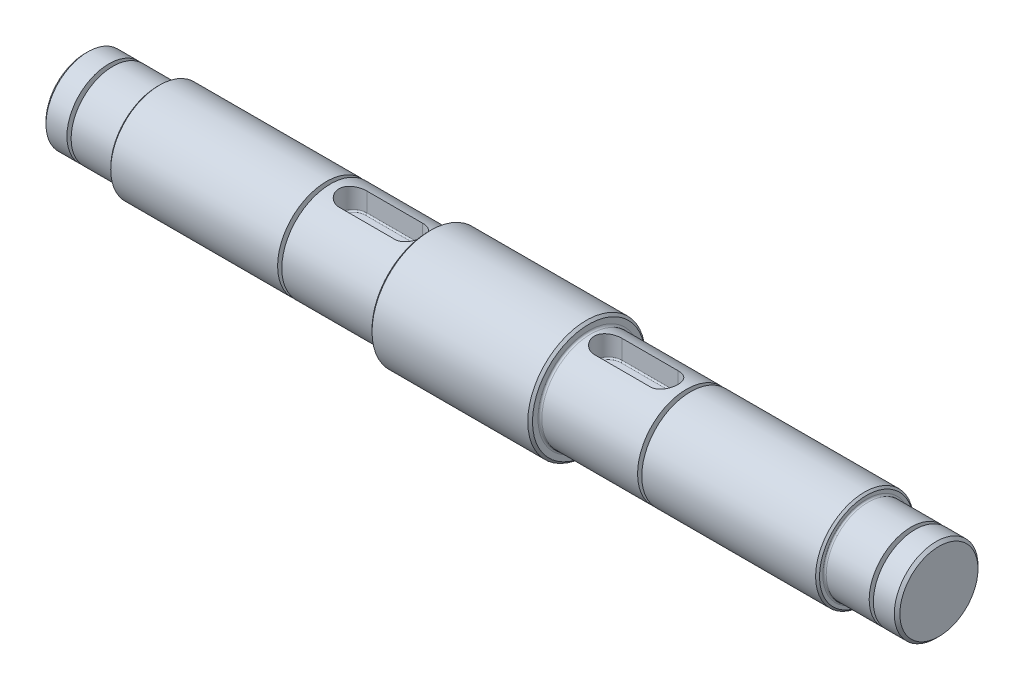
SolidWorks part; units mm, degrees
ref_plane "Front Plane" through (0, 0, 0) normal (0, 0, 1) x (1, 0, 0)
ref_plane "Top Plane" through (0, 0, 0) normal (0, 1, 0) x (1, 0, 0)
ref_plane "Right Plane" through (0, 0, 0) normal (1, 0, 0) x (0, 0, -1)
sketch "Sketch1" plane through (0, 0, 0) normal (0, 0, 1) x (1, 0, 0)
  line L0 (-143, 0) -> (143, 0) construction
  line L1 (-143, 0) -> (-143, 15)
  line L2 (-143, 15) -> (-127, 15)
  line L3 (-127, 15) -> (-127, 17.5)
  line L4 (-127, 17.5) -> (-66.5, 17.5)
  line L5 (-30, 17.5) -> (-30, 21)
  line L6 (-30, 21) -> (27.5, 21)
  line L7 (27.5, 21) -> (27.5, 17.5)
  line L8 (27.5, 17.5) -> (62.5, 17.5)
  line L9 (127, 17.5) -> (127, 15)
  line L10 (127, 15) -> (143, 15)
  line L11 (143, 15) -> (143, 0)
  line L12 (143, 0) -> (-143, 0)
  line L13 (-65, 17.5) -> (-65, 0) construction
  line L14 (-65, 17.5) -> (-30, 17.5)
  line L15 (62.5, 17.5) -> (62.5, 0) construction
  line L16 (64, 17.5) -> (127, 17.5)
  line L17 (-65, 17.5) -> (-65, 13.6)
  line L18 (-65, 13.6) -> (-66.5, 13.6)
  line L19 (-66.5, 13.6) -> (-66.5, 17.5)
  line L20 (62.5, 17.5) -> (62.5, 13.6)
  line L21 (62.5, 13.6) -> (64, 13.6)
  line L22 (64, 13.6) -> (64, 17.5)
  point P4 (0, 0)
  dimension "D13" = 3.9
  dimension "D15" = 3.9
  dimension "D1" = 286
  dimension "D2" = 16
  dimension "D3" = 99.5
  dimension "D4" = 15
  dimension "D5" = 17.5
  dimension "D6" = 21
  dimension "D7" = 57.5
  dimension "D8" = 17.5
  dimension "D9" = 97
  dimension "D10" = 16
  dimension "D11" = 15
  dimension "D12" = 35
  dimension "D14" = 35
  dimension "D16" = 1.5
  dimension "D17" = 1.5
revolve "Revolve1" add sketch "Sketch1" angle 360 about L0
fillet "Fillet1" [suppressed] radius 3
fillet "Fillet2" [suppressed] radius 3
fillet "Fillet3" [suppressed] radius 2.3
fillet "Fillet4" [suppressed] radius 2.3
sketch "Sketch2" plane through (-143, 0, 0) normal (-1, 0, 0) x (0, 0, 1)
  circle A1 centre (0, 0) radius 15
  circle A2 centre (0, 0) radius 15
  dimension "D1" = 0
extrude "Boss-Extrude1" add sketch "Sketch2" along normal blind 10 separate body
sketch "Sketch4" plane through (0, 0, 0) normal (0, 0, 1) x (1, 0, 0)
  line L0 (-143, 15) -> (-143, 11.5)
  line L1 (-143, 15) -> (-143, -15) construction
  line L2 (-143, 11.5) -> (-144.5, 11.5)
  line L3 (-144.5, 11.5) -> (-144.5, 15)
  line L4 (-143, 15) -> (-153, 15) construction
  line L5 (-144.5, 15) -> (-143, 15)
  line L6 (-153, 0) -> (0, 0) construction
  line L7 (-153, 15) -> (-153, -15) construction
  dimension "D1" = 1.5
  dimension "D2" = 3.5
revolve "Cut-Revolve1" cut sketch "Sketch4" angle 360 about L6
sketch "Sketch5" plane through (143, 0, 0) normal (1, 0, 0) x (0, 0, -1)
  circle A1 centre (0, 0) radius 15
  circle A2 centre (0, 0) radius 15
  dimension "D1" = 0
extrude "Boss-Extrude2" add sketch "Sketch5" along normal blind 10 separate body
sketch "Sketch6" plane through (0, 0, 0) normal (0, 0, 1) x (1, 0, 0)
  line L0 (143, 15) -> (143, 11.5)
  line L1 (143, 15) -> (143, -15) construction
  line L2 (143, 11.5) -> (144.5, 11.5)
  line L3 (144.5, 11.5) -> (144.5, 15)
  line L4 (153, 15) -> (143, 15) construction
  line L5 (144.5, 15) -> (143, 15)
  line L6 (-153, 0) -> (153, 0) construction
  line L7 (-153, 15) -> (-153, -15) construction
  line L8 (153, -15) -> (153, 15) construction
  dimension "D1" = 3.5
  dimension "D2" = 1.5
revolve "Cut-Revolve2" cut sketch "Sketch6" angle 360 about L6
ref_plane "Plane1" through (-37, 0, 0) normal (-1, 0, 0) x (0, 0, 1)
sketch "Sketch7" plane through (-37, 0, 0) normal (-1, 0, 0) x (0, 0, 1)
  line L0 (0, 17.5) -> (0, 0) construction
  line L1 (0, 17.5) -> (0, 9.5) construction
  line L2 (-5, 9.5) -> (5, 9.5)
  line L3 (5, 9.5) -> (5, 16.7705)
  line L4 (-5, 9.5) -> (-5, 16.7705)
  circle A0 centre (0, 0) radius 17.5 construction
  arc A1 (5, 16.7705) -> (-5, 16.7705) centre (0, 0) ccw
  point P8 (0, 9.5)
  dimension "D1" = 8
  dimension "D2" = 10
extrude "Cut-Extrude1" cut sketch "Sketch7" along normal blind 20
ref_plane "Plane2" through (34.5, 0, 0) normal (1, 0, 0) x (0, 0, -1)
sketch "Sketch8" plane through (34.5, 0, 0) normal (1, 0, 0) x (0, 0, -1)
  line L0 (0, 0) -> (0, 17.5) construction
  line L1 (0, 17.5) -> (0, 9.5) construction
  line L2 (-5, 9.5) -> (5, 9.5)
  line L3 (5, 9.5) -> (5, 16.7705)
  line L4 (-5, 9.5) -> (-5, 16.7705)
  circle A0 centre (0, 0) radius 17.5 construction
  arc A1 (5, 16.7705) -> (-5, 16.7705) centre (0, 0) ccw
  point P8 (0, 9.5)
  dimension "D1" = 10
  dimension "D2" = 8
extrude "Cut-Extrude2" cut sketch "Sketch8" along normal blind 20
fillet "Fillet5" radius 0.6 1 edges at (-127, 0, 15)
chamfer "Chamfer1" distance 0.7 angle 45 1 edges at (-127, 0, 17.5)
fillet "Fillet6" radius 0.7 1 edges at (-30, 0, 17.5)
chamfer "Chamfer2" distance 0.84 angle 45 1 edges at (-30, 0, 21)
fillet "Fillet7" radius 0.7 1 edges at (27.5, 0, 17.5)
chamfer "Chamfer3" distance 0.84 angle 45 1 edges at (27.5, 0, 21)
chamfer "Chamfer4" distance 0.7 angle 45 1 edges at (127, 0, 17.5)
fillet "Fillet8" radius 0.6 1 edges at (127, 0, 15)
ref_plane "Plane3" through (0, 17.5, 0) normal (0, 1, 0) x (1, 0, 0)
sketch "Sketch10" plane through (0, 17.5, 0) normal (0, 1, 0) x (1, 0, 0)
  line L0 (-57, 5) -> (-57, -5) construction
  line L1 (-37, 5) -> (-37, -5) construction
  line L2 (-57, 5) -> (-57, -5)
  line L3 (-37, 5) -> (-37, -5)
  arc A0 (-57, 5) -> (-57, -5) centre (-57, 0) ccw
  arc A1 (-37, -5) -> (-37, 5) centre (-37, 0) ccw
  dimension "D1" = 10
extrude "Cut-Extrude3" cut sketch "Sketch10" against normal up to surface (8 mm away) up to face at (-47, 9.5, 0)
ref_plane "Plane4" through (0, 17.5, 0) normal (0, 1, 0) x (1, 0, 0)
sketch "Sketch11" plane through (0, 17.5, 0) normal (0, 1, 0) x (1, 0, 0)
  line L0 (34.5, -5) -> (34.5, 5) construction
  line L1 (54.5, -5) -> (54.5, 5) construction
  line L2 (34.5, 5) -> (34.5, -5)
  line L3 (54.5, 5) -> (54.5, -5)
  arc A0 (34.5, 5) -> (34.5, -5) centre (34.5, 0) ccw
  arc A1 (54.5, -5) -> (54.5, 5) centre (54.5, 0) ccw
extrude "Cut-Extrude4" cut sketch "Sketch11" against normal up to surface (8 mm away) up to face at (44.5, 9.5, 0)
fillet "Fillet9" radius 0.4 1 edges at (144.5, 0, 11.5)
sketch "Sketch12" plane through (0, 0, 0) normal (0, 0, 1) x (1, 0, 0)
  line L0 (153, 0) -> (64, 0) construction
  line L1 (153, -15) -> (153, 15) construction
  line L2 (64, 13.6) -> (64, -13.6) construction
  line L6 (143, 11.9) -> (143, 11.5)
  line L7 (143.4, 11.5) -> (143, 11.5)
  arc A0 (143.4, 11.5) -> (143, 11.9) centre (143.4, 11.9) cw
  dimension "D1" = 0.4
revolve "Revolve2" add sketch "Sketch12" angle 360 about L0
fillet "Fillet10" radius 0.4 2 edges at (62.5, 0, 13.6) (64, 0, 13.6)
fillet "Fillet11" radius 0.4 2 edges at (-66.5, 0, 13.6) (-65, 0, 13.6)
fillet "Fillet12" radius 0.4 1 edges at (-144.5, 0, 11.5)
sketch "Sketch13" plane through (0, 0, 0) normal (0, 0, 1) x (1, 0, 0)
  line L0 (-153, 0) -> (-66.5, 0) construction
  line L1 (-153, 15) -> (-153, -15) construction
  line L2 (-66.5, -14) -> (-66.5, 14) construction
  line L6 (-143.4, 11.5) -> (-143, 11.5)
  line L7 (-143, 11.5) -> (-143, 11.9)
  arc A0 (-143.4, 11.5) -> (-143, 11.9) centre (-143.4, 11.9) ccw
  dimension "D1" = 0.4
revolve "Revolve3" add sketch "Sketch13" angle 360 about L0
fillet "Fillet13" radius 0.5 8 edges at (44.5, 9.5, 5) (59.5, 9.5, 0) (44.5, 9.5, -5) (-47, 9.5, 5) (-32, 9.5, 0) (-47, 9.5, -5) (29.5, 9.5, 0) (-62, 9.5, 0)
chamfer "Chamfer5" distance 1 angle 45 1 edges at (153, 0, -15)
chamfer "Chamfer6" distance 1 angle 45 1 edges at (-153, 0, 15)
